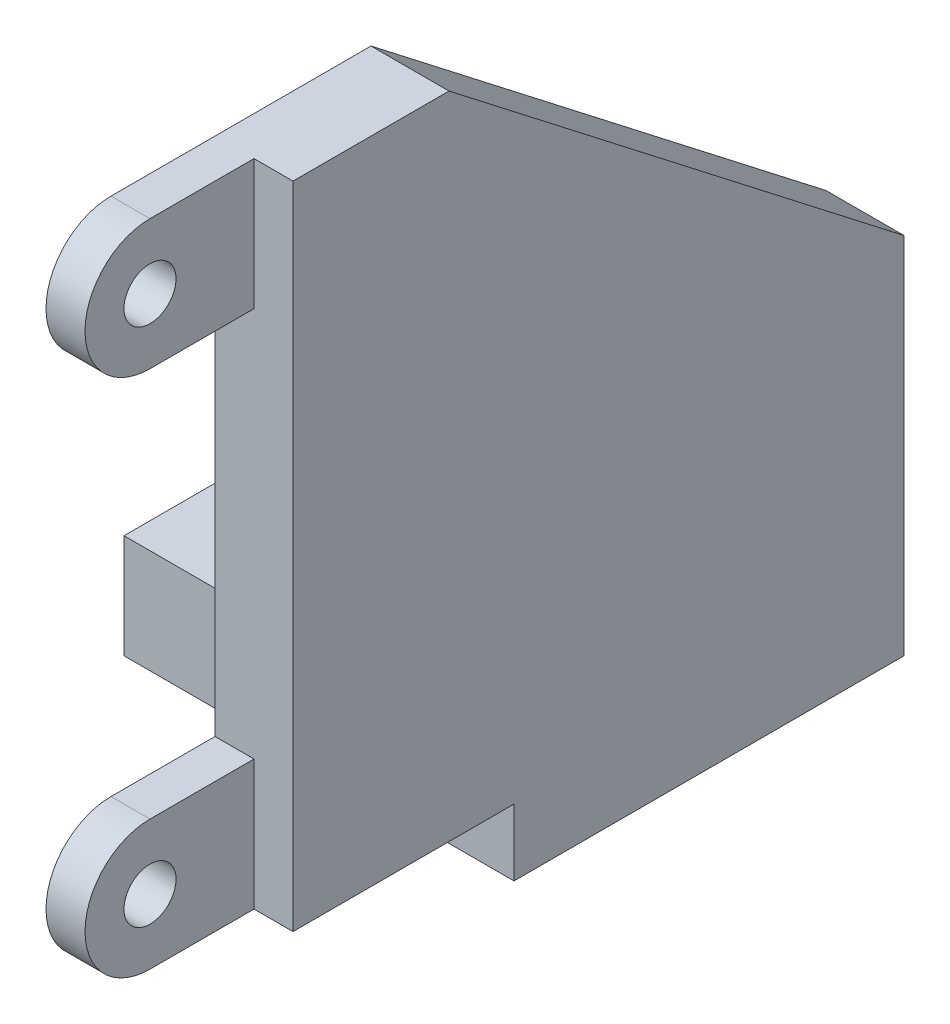
SolidWorks part; units mm, degrees
ref_plane "前视基准面" through (0, 0, 0) normal (0, 0, 1) x (1, 0, 0)
ref_plane "上视基准面" through (0, 0, 0) normal (0, 1, 0) x (1, 0, 0)
ref_plane "右视基准面" through (0, 0, 0) normal (1, 0, 0) x (0, 0, -1)
sketch "草图1" plane through (0, 0, 0) normal (0, 1, 0) x (1, 0, 0)
  line L1 (0, 15) -> (-30, 15)
  line L2 (0, 15) -> (0, -15)
  line L3 (0, -15) -> (-30, -15)
  line L4 (-30, 15) -> (-30, -15)
  circle A1 centre (-17, 7.5) radius 2
  circle A2 centre (-17, -7.5) radius 2
  point P4 (-30, 0)
  point P7 (0, 0)
  point P9 (0, 0)
  point P10 (0, 0)
  point P13 (0, 0)
  point P14 (0, 9.2782)
  point P17 (0, 0)
  point P18 (0.6649, -22.2805)
  dimension "D3" = 4
  dimension "D1" = 30
  dimension "D2" = 30
  dimension "D4" = 13
  dimension "D5" = 7.5
  dimension "D6" = 15
extrude "凸台-拉伸1" add sketch "草图1" along normal blind 8
sketch "草图3" plane through (0, 0, 0) normal (1, 0, 0) x (0, 0, -1)
  line L0 (-15, 8) -> (-15, 5.125)
  line L1 (-15, 5.125) -> (-40, 5.125)
  line L3 (-40, 15.125) -> (-32, 15.125)
  line L4 (-32, 15.125) -> (-32, 45.125)
  line L5 (-32, 45.125) -> (-40, 45.125)
  line L7 (-40, 55.125) -> (-20, 55.125)
  line L8 (-20, 55.125) -> (15, 28)
  line L9 (15, 28) -> (15, 8)
  line L10 (-15, 8) -> (15, 8)
  line L11 (-15, 0) -> (15, 0) construction
  arc A0 (-40, 15.125) -> (-40, 5.125) centre (-40, 10.125) ccw
  arc A1 (-40, 55.125) -> (-40, 45.125) centre (-40, 50.125) ccw
  circle A2 centre (-40, 10.125) radius 2
  circle A3 centre (-40, 50.125) radius 2
  point P17 (-40, 17.0124)
  dimension "D5" = 5
  dimension "D7" = 4
  dimension "D1" = 25
  dimension "D2" = 8
  dimension "D3" = 20
  dimension "D4" = 10.125
  dimension "D6" = 40
  dimension "D8" = 20
extrude "凸台-拉伸2" add sketch "草图3" against normal blind 6
chamfer "倒角1" distance 3 angle 45 2 edges at (-17, 8, -9.5) (-17, 8, 9.5)
sketch "草图4" plane through (-6, 0, 0) normal (-1, 0, 0) x (0, 0, 1)
  line L0 (40, 5.125) -> (15, 5.125) construction
  line L1 (32, 5.125) -> (45, 5.125)
  line L2 (32, 5.125) -> (32, 55.125)
  line L3 (32, 55.125) -> (45, 55.125)
  line L4 (45, 5.125) -> (45, 55.125)
  line L5 (20, 55.125) -> (40, 55.125) construction
  line L6 (32, 45.125) -> (32, 15.125) construction
  arc A2 (40, 45.125) -> (40, 55.125) centre (40, 50.125) ccw construction
extrude "切除-拉伸1" cut sketch "草图4" along normal blind 3 from surface at -6 starting at face at (0, 24.4545, 23.0909)
